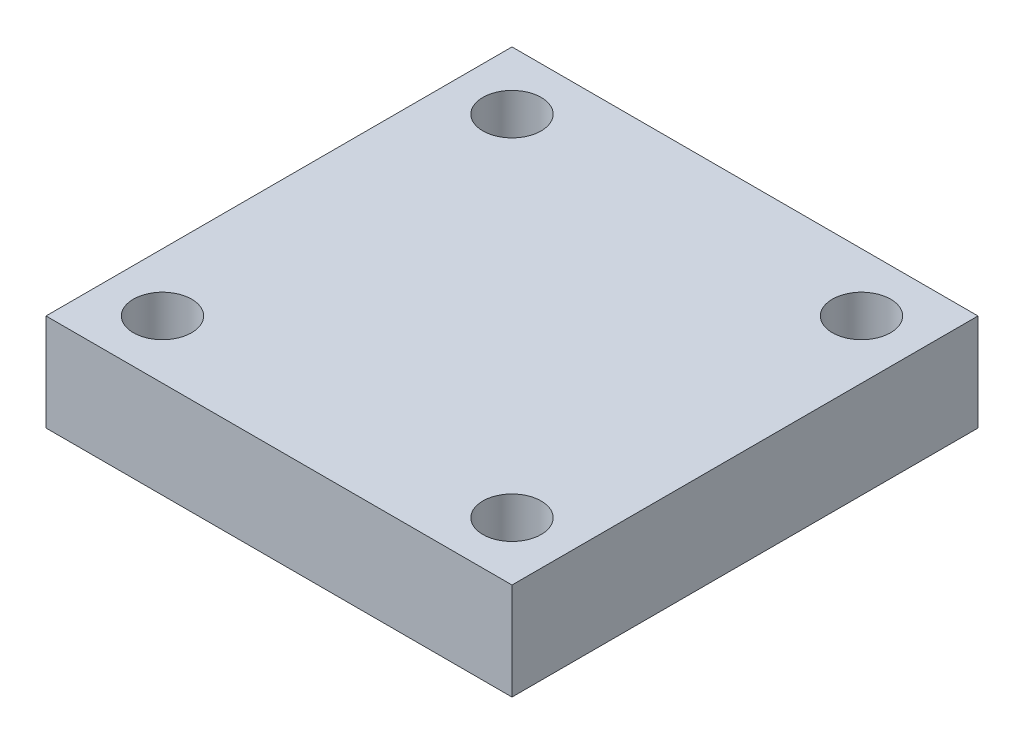
SolidWorks part; units mm, degrees
ref_plane "前视基准面" through (0, 0, 0) normal (0, 0, 1) x (1, 0, 0)
ref_plane "上视基准面" through (0, 0, 0) normal (0, 1, 0) x (1, 0, 0)
ref_plane "右视基准面" through (0, 0, 0) normal (1, 0, 0) x (0, 0, -1)
other "Configuration Table"
sketch "草图1" plane through (0, 0, 0) normal (0, 1, 0) x (1, 0, 0)
  line L1 (-6.1885, 14.1407) -> (17.8115, 14.1407)
  line L2 (-6.1885, 14.1407) -> (-6.1885, -9.8593)
  line L3 (-6.1885, -9.8593) -> (17.8115, -9.8593)
  line L4 (17.8115, 14.1407) -> (17.8115, -9.8593)
  dimension "D1" = 24
  dimension "D2" = 24
extrude "凸台-拉伸1" add sketch "草图1" along normal blind 5
sketch "草图2" plane through (0, 0, 0) normal (0, 1, 0) x (1, 0, 0)
  line L0 (-6.1885, 2.1407) -> (49993.8115, 2.1407) construction
  line L1 (-6.1885, 14.1407) -> (-6.1885, -9.8593) construction
  line L2 (17.8115, 14.1407) -> (-6.1885, 14.1407) construction
  line L3 (5.8115, 14.1407) -> (5.8115, -49985.8593) construction
  circle A0 centre (-3.1885, 11.1407) radius 1.5
  circle A1 centre (-3.1885, -6.8593) radius 1.5
  circle A2 centre (14.8115, -6.8593) radius 1.5
  circle A3 centre (14.8115, 11.1407) radius 1.5
  point P6 (-6.1885, 2.1407)
  point P13 (5.8115, 14.1407)
  dimension "D1" = 3
  dimension "D2" = 3
  dimension "D3" = 3
extrude "切除-拉伸1" cut sketch "草图2" along normal through all
